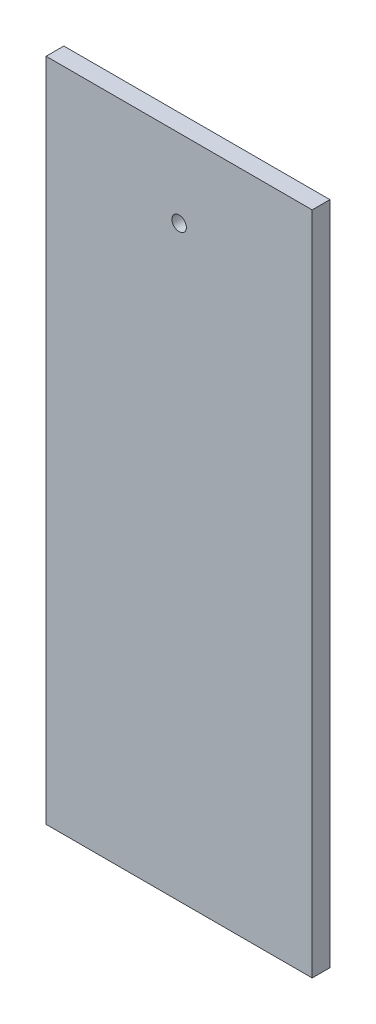
SolidWorks part; units mm, degrees
ref_plane "Front Plane" through (0, 0, 0) normal (0, 0, 1) x (1, 0, 0)
ref_plane "Top Plane" through (0, 0, 0) normal (0, 1, 0) x (1, 0, 0)
ref_plane "Right Plane" through (0, 0, 0) normal (1, 0, 0) x (0, 0, -1)
sketch "Sketch1" plane through (0, 0, 0) normal (0, 0, 1) x (1, 0, 0)
  line L1 (0, 0) -> (30, 0)
  line L2 (0, 0) -> (0, 75)
  line L3 (0, 75) -> (30, 75)
  line L4 (30, 0) -> (30, 75)
  line L5 (15, 75) -> (15, 67) construction
  circle A0 centre (15, 66.185) radius 0.815
  dimension "D3" = 1.63
  dimension "D1" = 75
  dimension "D2" = 30
  dimension "D4" = 8
extrude "Boss-Extrude1" add sketch "Sketch1" along normal blind 2
